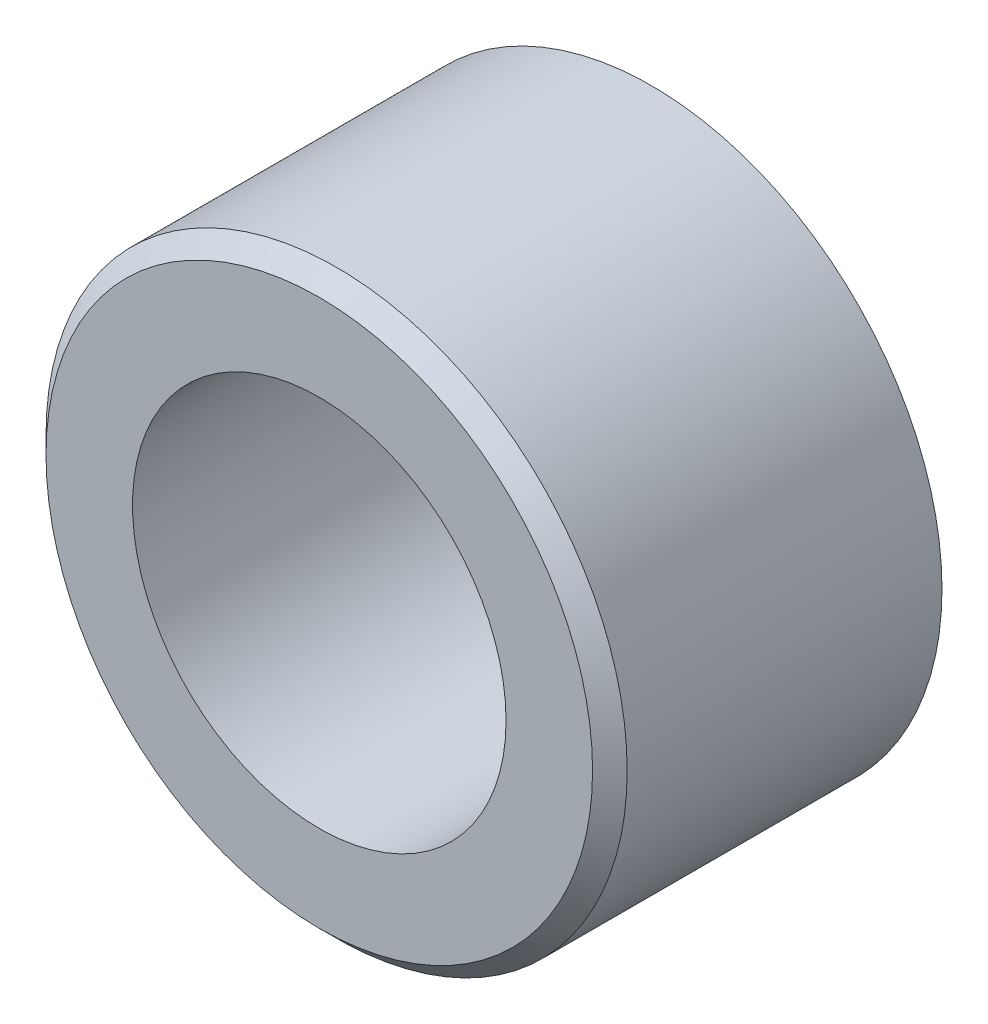
SolidWorks part; units mm, degrees
ref_plane "Front Plane" through (0, 0, 0) normal (0, 0, 1) x (1, 0, 0)
ref_plane "Top Plane" through (0, 0, 0) normal (0, 1, 0) x (1, 0, 0)
ref_plane "Right Plane" through (0, 0, 0) normal (1, 0, 0) x (0, 0, -1)
sketch "Sketch1" plane through (0, 0, 0) normal (0, 0, 1) x (1, 0, 0)
  line L0 (0, 3.5712) -> (0, 5.5562) construction
  circle A0 centre (0, 0) radius 5.5562
  circle A1 centre (0, 0) radius 3.5712
  dimension "D1" = 1.985
  dimension "OD" = 11.1125
  dimension "ID" = 7.1425
extrude "Extrude1" add sketch "Sketch1" along normal mid plane 6.35
chamfer "Chamfer1" distance 0.3308 angle 45 1 edges at (5.5562, 0, 3.175)
sketch "Sketch6" plane through (0, 0, 3.175) normal (0, 0, -1) x (-1, 0, 0)
  line L0 (0, 0) -> (-3.5712, 0) construction
  line L1 (0, 0) -> (2.5252, 2.5252) construction
  circle A0 centre (0, 0) radius 3.5712 construction
  circle A3 centre (0, 0) radius 3.5712
  dimension "D1" = 135
equation "\"D1@Chamfer1\" = \"D1@Sketch1\"/6"
